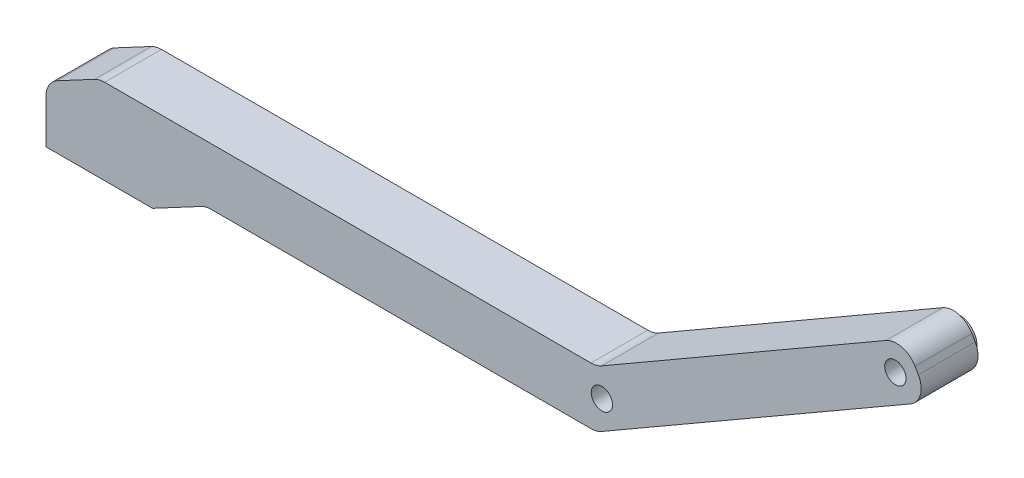
SolidWorks part; units mm, degrees
ref_plane "前视基准面" through (0, 0, 0) normal (0, 0, 1) x (1, 0, 0)
ref_plane "上视基准面" through (0, 0, 0) normal (0, 1, 0) x (1, 0, 0)
ref_plane "右视基准面" through (0, 0, 0) normal (1, 0, 0) x (0, 0, -1)
sketch "草图1" plane through (0, 0, 0) normal (0, 0, 1) x (1, 0, 0)
  line L2 (-7.5, 4) -> (-7.5, -4)
  line L3 (-7.5, -4) -> (7.5, -4)
  line L5 (-7.5, 4) -> (7.5, -4) construction
  line L6 (-7.5, -4) -> (7.5, 4) construction
  line L8 (0, 8) -> (70, 8)
  line L10 (0, 8) -> (-7.5, 4)
  line L11 (7.5, -4) -> (15, 0)
  line L12 (70, 0) -> (116.7654, 27)
  line L13 (116.7654, 27) -> (113.3013, 33)
  line L14 (70, 8) -> (113.3013, 33)
  line L15 (15, 0) -> (70, 0)
  circle A0 centre (112.0369, 28.27) radius 1.5
  circle A1 centre (70.7275, 4.42) radius 1.5
  point P0 (0, 0)
extrude "凸台-拉伸1" add sketch "草图1" along normal blind 8
fillet "圆角1" radius 3 7 edges at (15, 0, 4) (113.3013, 33, 4) (116.7654, 27, 4) (70, 0, 4) (70, 8, 4) (0, 8, 4) (-7.5, 4, 4)
sketch "草图2" plane through (0, 0, 8) normal (0, 0, 1) x (1, 0, 0)
  circle A1 centre (112.0369, 28.27) radius 2.5
  circle A3 centre (112.0369, 28.27) radius 1.5
extrude "凸台-拉伸2" add sketch "草图2" against normal blind 9
